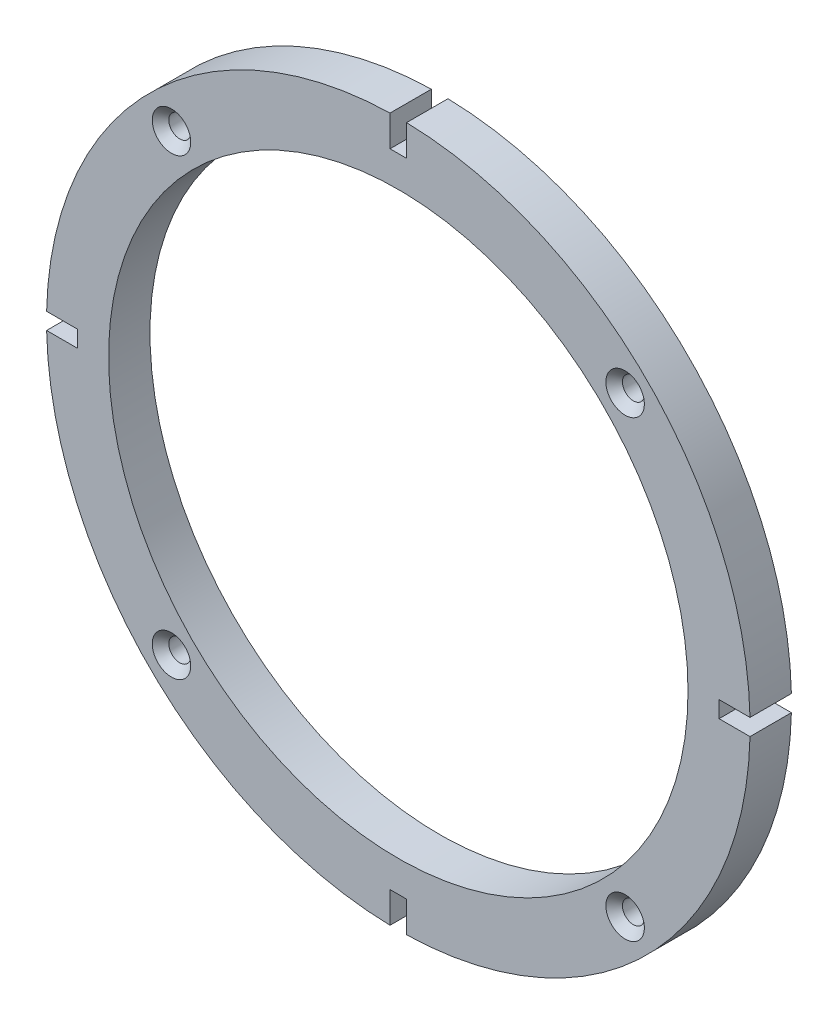
SolidWorks part; units mm, degrees
material "6063-T6"
ref_plane "Płaszczyzna przednia" through (0, 0, 0) normal (0, 0, 1) x (1, 0, 0)
ref_plane "Płaszczyzna górna" through (0, 0, 0) normal (0, 1, 0) x (1, 0, 0)
ref_plane "Płaszczyzna prawa" through (0, 0, 0) normal (1, 0, 0) x (0, 0, -1)
sketch "Sketch1" plane through (0, 0, 0) normal (0, 0, 1) x (1, 0, 0)
  line L0 (84.9765, -2) -> (77.4996, -2)
  line L1 (-2, 77.4996) -> (2, 77.4996)
  line L2 (-2, 77.4996) -> (-2, 84.9765)
  line L4 (2, 84.9765) -> (2, 77.4996)
  line L5 (77.4996, 2) -> (84.9765, 2)
  line L6 (77.4996, 2) -> (77.4996, -2)
  line L7 (-2, -84.9765) -> (-2, -77.4996)
  line L8 (2, -77.4996) -> (2, -84.9765)
  line L9 (2, -77.4996) -> (-2, -77.4996)
  line L10 (-84.9765, 2) -> (-77.4996, 2)
  line L11 (-77.4996, -2) -> (-84.9765, -2)
  line L12 (-77.4996, -2) -> (-77.4996, 2)
  circle A0 centre (0, 0) radius 70
  arc A1 (-2, 84.9765) -> (-84.9765, 2) centre (0, 0) ccw
  arc A2 (-84.9765, -2) -> (-2, -84.9765) centre (0, 0) ccw
  arc A3 (2, -84.9765) -> (84.9765, -2) centre (0, 0) ccw
  arc A4 (84.9765, 2) -> (2, 84.9765) centre (0, 0) ccw
  point P6 (-2, 77.4996)
  point P7 (2, 77.4996)
  point P24 (0, 0)
  dimension "D1" = 170
  dimension "D2" = 140
  dimension "D3" = 77.4996
  dimension "D4" = 2
  dimension "D5" = 4
  dimension "D6" = 4
extrude "Boss-Extrude1" add sketch "Sketch1" along normal blind 10 contours A0 | A1 L10 L12 L11 A2 L7 L9 L8 A3 L0 L6 L5 A4 L4 L1 L2
sketch "Sketch2" plane through (0, 0, 0) normal (0, 0, -1) x (-1, 0, 0)
  line L0 (0, 0) -> (-73.6832, 73.6832) construction
  line L1 (0, 0) -> (0, 118.1493) construction
  circle A0 centre (-54.8008, 54.8008) radius 2.65
  arc A1 (-2, 84.9765) -> (-84.9765, 2) centre (0, 0) ccw construction
  circle A2 centre (54.8008, 54.8008) radius 2.65
  circle A3 centre (54.8008, -54.8008) radius 2.65
  circle A4 centre (-54.8008, -54.8008) radius 2.65
  point P18 (0, 0)
  dimension "D3" = 5.3
  dimension "D1" = 77.5
  dimension "D2" = 45
  dimension "D4" = 4
extrude "Wytnij-wyciągnięcie1" cut sketch "Sketch2" against normal blind 10
sketch "Szkic1" plane through (0, 0, 0) normal (0, 0, -1) x (-1, 0, 0)
  circle A0 centre (-54.8008, 54.8008) radius 5
  dimension "D1" = 10
extrude "Wytnij-wyciągnięcie2" cut sketch "Szkic1" against normal blind 2 contours A0
pattern_circular "Szyk kołowy1" count 4 over 360 about axis through (0, 0, 0) along (0, 0, 1) of "Wytnij-wyciągnięcie2"
chamfer "Sfazowanie1" distance 2 4 edges at (52.1508, -54.8008, 10) (52.1508, 54.8008, 10) (-57.4508, 54.8008, 10) (-57.4508, -54.8008, 10)
